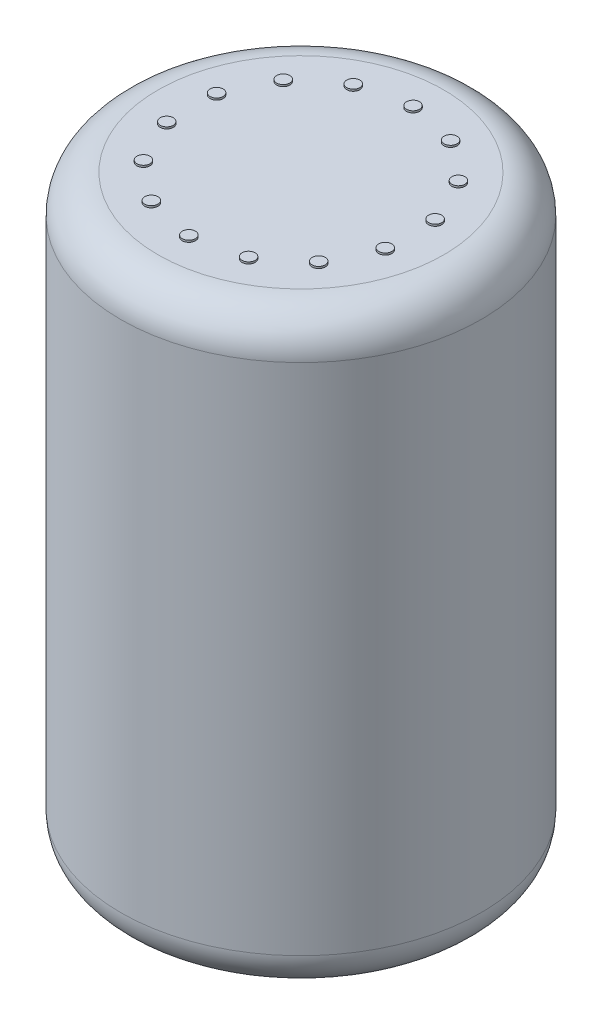
SolidWorks part; units mm, degrees
material "Glass"
ref_plane "Front Plane" through (0, 0, 0) normal (0, 0, 1) x (1, 0, 0)
ref_plane "Top Plane" through (0, 0, 0) normal (0, 1, 0) x (1, 0, 0)
ref_plane "Right Plane" through (0, 0, 0) normal (1, 0, 0) x (0, 0, -1)
sketch "Sketch1" plane through (0, 0, 0) normal (0, 1, 0) x (1, 0, 0)
  circle A0 centre (0, 0) radius 9.65
  dimension "D1" = 19.3
extrude "Boss-Extrude1" add sketch "Sketch1" along normal blind 31.5
fillet "Fillet4" radius 2 2 edges at (0, 0, 9.65) (0, 31.5, 9.65)
sketch "Sketch2" plane through (0, 31.5, 0) normal (0, 1, 0) x (1, 0, 0)
  line L0 (0, 0) -> (0, 6) construction
  circle A0 centre (0, 6) radius 0.35
  dimension "D1" = 6
extrude "Boss-Extrude2" add sketch "Sketch2" along normal blind 0.1
pattern_circular "CirPattern1" count 14 over 360 about axis through (0, 0, 0) along (0, 1, 0) of "Boss-Extrude2"
